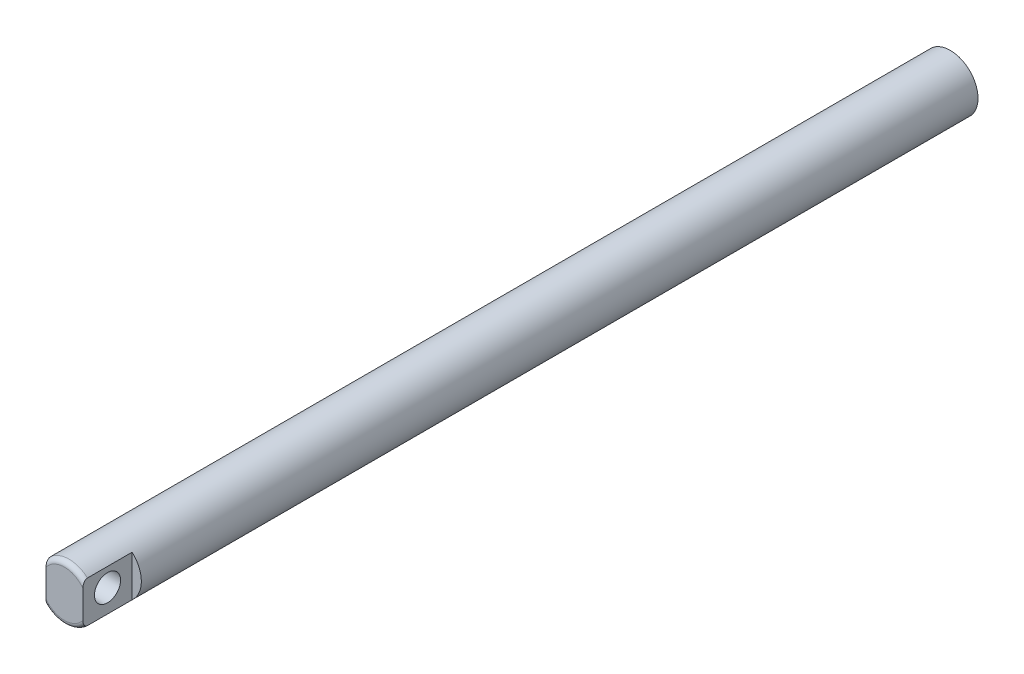
SolidWorks part; units mm, degrees
material "AISI 316 Stainless Steel Sheet (SS)"
ref_plane "Front Plane" through (0, 0, 0) normal (0, 0, 1) x (1, 0, 0)
ref_plane "Top Plane" through (0, 0, 0) normal (0, 1, 0) x (1, 0, 0)
ref_plane "Right Plane" through (0, 0, 0) normal (1, 0, 0) x (0, 0, -1)
sketch "Sketch1" plane through (0, 0, 0) normal (0, 0, 1) x (1, 0, 0)
  circle A0 centre (0, 0) radius 4.5
extrude "Boss-Extrude1" add sketch "Sketch1" along normal blind 144
sketch "Sketch3" plane through (0, 0, 0) normal (1, 0, 0) x (0, 0, -1)
  line L0 (-144, 4.5) -> (-144, -4.5) construction
  line L1 (-144, 4.5) -> (-144, -4.5)
  line L2 (-136, 4.5) -> (-136, -4.5)
  line L4 (-136, 4.5) -> (-144, 4.5)
  line L5 (-144, -4.5) -> (-136, -4.5)
  dimension "D1" = 8
  dimension "D2" = 9
extrude "Cut-Extrude1" cut sketch "Sketch3" against normal blind 1.5 from offset 3 offset against normal yes
mirror "Mirror1" about plane through (0, 0, 0) normal (1, 0, 0) of "Cut-Extrude1"
fillet "Fillet1" radius 0.75 2 edges at (0, 4.5, 144) (0, -4.5, 144)
sketch "Sketch4" plane through (3, 0, 0) normal (1, 0, 0) x (0, 0, -1)
  line L0 (-144, 2.25) -> (-144, -2.25) construction
  line L1 (-143.25, 3.3541) -> (-136, 3.3541) construction
  circle A0 centre (-140, 0.3541) radius 2.125
  dimension "D1" = 4
  dimension "D2" = 3
extrude "Cut-Extrude2" cut sketch "Sketch4" against normal through all both and the other way through all
